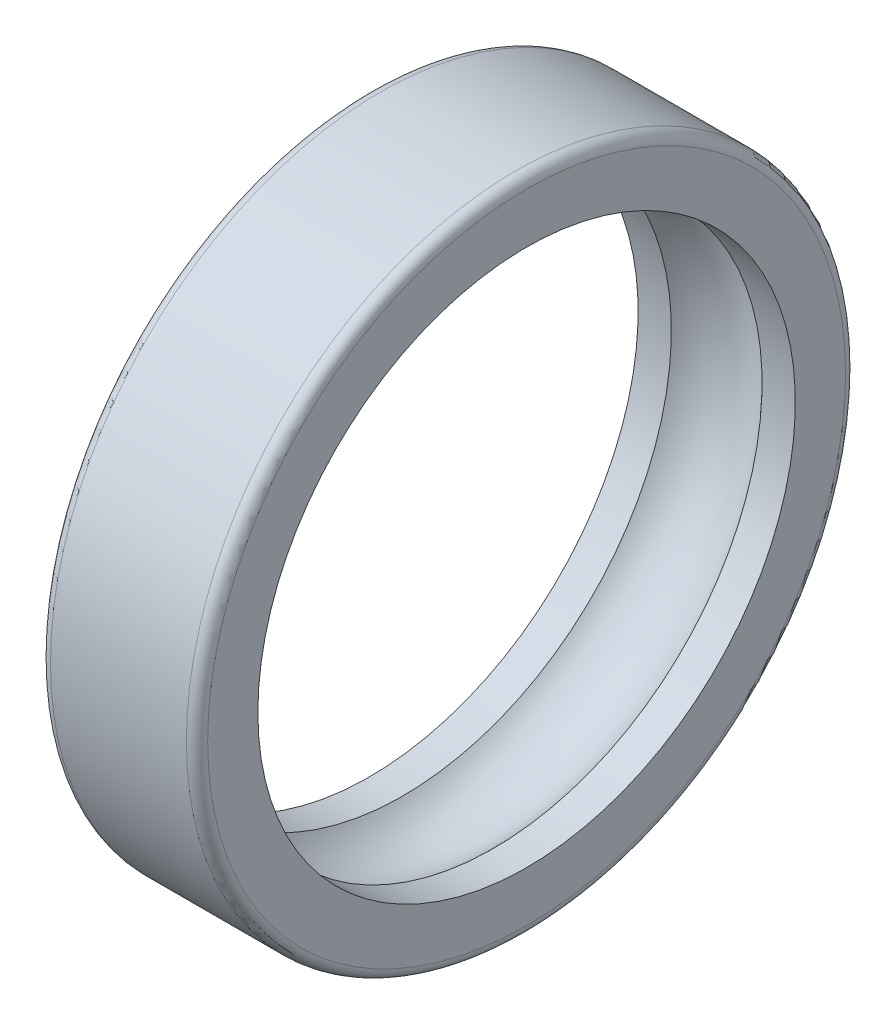
SolidWorks part; units mm, degrees
ref_plane "Front Plane" through (0, 0, 0) normal (0, 0, 1) x (1, 0, 0)
ref_plane "Top Plane" through (0, 0, 0) normal (0, 1, 0) x (1, 0, 0)
ref_plane "Right Plane" through (0, 0, 0) normal (1, 0, 0) x (0, 0, -1)
sketch "Sketch1" plane through (0, 0, 0) normal (0, 0, 1) x (1, 0, 0)
  line L0 (-25.3585, 0) -> (48.5277, 0) construction
  line L1 (0, 0) -> (0, 53) construction
  line L2 (-15.5, 65) -> (15.5, 65)
  line L3 (-15.5, 65) -> (-15.5, 53)
  line L4 (-15.5, 53) -> (-8.9443, 53)
  line L5 (15.5, 65) -> (15.5, 53)
  line L6 (-15.5, 65) -> (15.5, 53) construction
  line L7 (-15.5, 53) -> (15.5, 65) construction
  line L8 (8.9443, 53) -> (15.5, 53)
  arc A0 (-8.9443, 53) -> (8.9443, 53) centre (0, 45) cw
  point P3 (0, 59)
  dimension "D4" = 12
  dimension "D1" = 31
  dimension "D2" = 53
  dimension "D3" = 65
  dimension "D5" = 8
revolve "Revolve1" add sketch "Sketch1" angle 360 about L0
fillet "Fillet1" radius 2.1 2 edges at (15.5, 0, 65) (-15.5, 0, 65)
scale "Scale1" scale about centroid uniform scaling yes scale factor 1.413611
